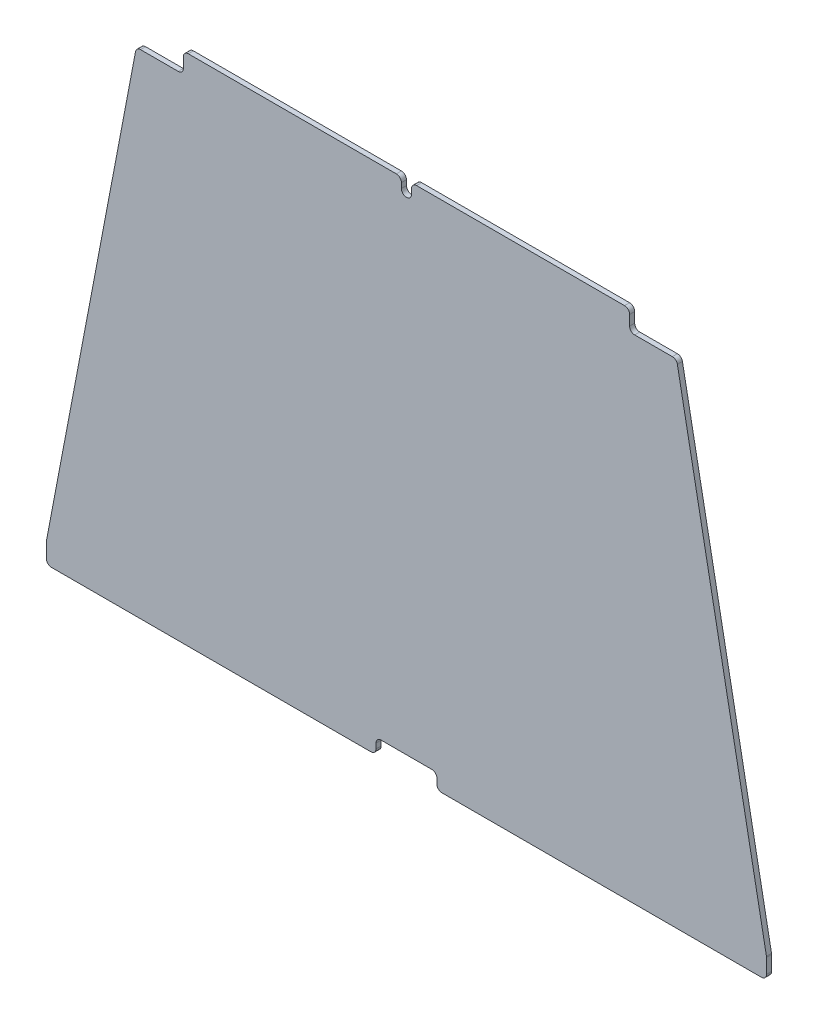
SolidWorks part; units mm, degrees
ref_plane "正面" through (0, 0, 0) normal (0, 0, 1) x (1, 0, 0)
ref_plane "平面" through (0, 0, 0) normal (0, 1, 0) x (1, 0, 0)
ref_plane "右側面" through (0, 0, 0) normal (1, 0, 0) x (0, 0, -1)
sketch "ｽｹｯﾁ2" plane through (0, 0, 0) normal (0, 0, 1) x (1, 0, 0)
  line L0 (0, 0) -> (0, 26.7695) construction
  line L1 (355, 0) -> (-355, 0)
  line L2 (-355, 0) -> (-355, 20)
  line L3 (-355, 20) -> (-262.5, 506)
  line L4 (-262.5, 506) -> (262.5, 506)
  line L5 (355, 20) -> (262.5, 506)
  line L6 (355, 0) -> (355, 20)
  point P11 (0, 506)
  point P13 (0, 0)
  dimension "D1" = 20
  dimension "D2" = 710
  dimension "D3" = 506
  dimension "D4" = 525
extrude "ﾎﾞｽ - 押し出し1" add sketch "ｽｹｯﾁ2" along normal blind 5
sketch "ｽｹｯﾁ3" plane through (0, 0, 5) normal (0, 0, 1) x (1, 0, 0)
  line L0 (-264.4033, 496) -> (264.4033, 496) construction
  line L1 (-262.5, 506) -> (-355, 20) construction
  line L2 (355, 20) -> (262.5, 506) construction
  line L3 (0, 506) -> (0, 0) construction
  line L4 (262.5, 506) -> (-262.5, 506) construction
  line L5 (-266.3066, 486) -> (-220, 486)
  line L6 (-220, 486) -> (-220, 506)
  line L7 (220, 486) -> (220, 506)
  line L8 (266.3066, 486) -> (220, 486)
  line L9 (-5, 496) -> (-5, 506)
  line L10 (5, 496) -> (5, 506)
  line L11 (-355, 20) -> (-355, 0)
  line L12 (-355, 0) -> (355, 0)
  line L13 (355, 0) -> (355, 20)
  line L14 (355, 20) -> (262.5, 506)
  line L15 (262.5, 506) -> (-262.5, 506)
  line L16 (-262.5, 506) -> (-355, 20)
  line L17 (-355, 20) -> (-355, 0)
  line L18 (-355, 0) -> (355, 0)
  line L19 (355, 0) -> (355, 20)
  line L20 (355, 20) -> (262.5, 506)
  line L21 (262.5, 506) -> (-262.5, 506)
  line L22 (-262.5, 506) -> (-355, 20)
  line L23 (0, 10) -> (25, 10) construction
  line L24 (25, 15) -> (-25, 15)
  line L25 (30, 10) -> (30, 0)
  line L26 (-30, 10) -> (-30, 0)
  line L27 (-30, 0) -> (30, 0)
  arc A0 (-220, 496) -> (-230, 496) centre (-225, 496) ccw construction
  arc A1 (-230, 496) -> (-220, 496) centre (-225, 496) ccw construction
  arc A2 (230, 496) -> (220, 496) centre (225, 496) cw construction
  arc A3 (220, 496) -> (230, 496) centre (225, 496) cw construction
  arc A4 (-5, 496) -> (5, 496) centre (0, 496) ccw
  arc A5 (0, 501) -> (-5, 496) centre (0, 496) ccw construction
  arc A6 (5, 496) -> (0, 501) centre (0, 496) ccw construction
  arc A7 (30, 10) -> (25, 15) centre (25, 10) ccw
  arc A8 (-30, 10) -> (-25, 15) centre (-25, 10) cw
  arc A9 (-25, 15) -> (-30, 10) centre (-25, 10) cw construction
  arc A10 (20, 10) -> (30, 10) centre (25, 10) ccw construction
  arc A11 (25, 15) -> (20, 10) centre (25, 10) ccw construction
  line M13 (355, 20) -> (262.5, 506)
  line M14 (262.5, 506) -> (-262.5, 506)
  line M15 (-262.5, 506) -> (-355, 20)
  dimension "D2" = 10
  dimension "D6" = 10
  dimension "D7" = 10
  dimension "D1" = 10
  dimension "D3" = 37.5
  dimension "D5" = 20
  dimension "D8" = 50
  dimension "D9" = 10
  dimension "D4" = 0
extrude "ｶｯﾄ - 押し出し1" cut sketch "ｽｹｯﾁ3" against normal through all contours L5 L6 M14 M15 | L8 L7 M13 M14 | L9 A4 L10 M14 | A8 L26 L18 L25 A7 L24
fillet "ﾌｨﾚｯﾄ1" radius 5 14 edges at (355, 20, 2.5) (-355, 20, 2.5) (-355, 0, 2.5) (355, 0, 2.5) (30, 0, 2.5) (-30, 0, 2.5) (266.3066, 486, 2.5) (220, 486, 2.5) (220, 506, 2.5) (5, 506, 2.5) (-5, 506, 2.5) (-220, 506, 2.5) (-220, 486, 2.5) (-266.3066, 486, 2.5)
